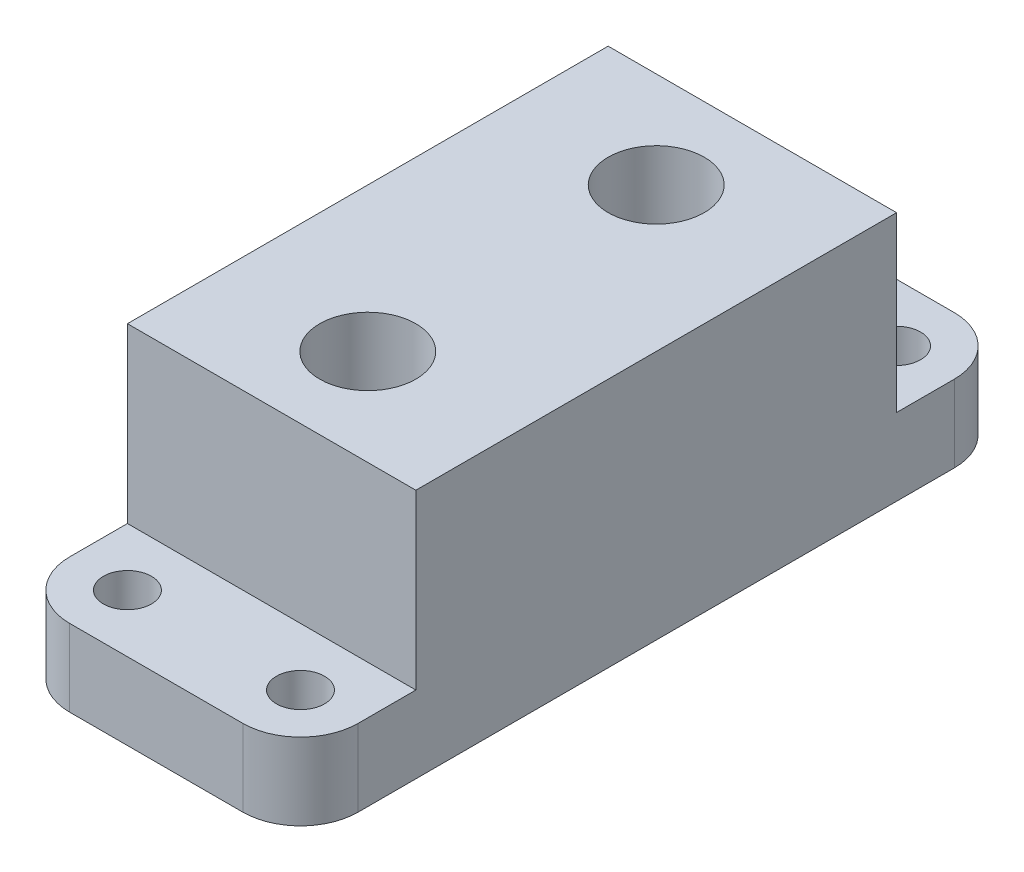
SolidWorks part; units mm, degrees
ref_plane "前视基准面" through (0, 0, 0) normal (0, 0, 1) x (1, 0, 0)
ref_plane "上视基准面" through (0, 0, 0) normal (0, 1, 0) x (1, 0, 0)
ref_plane "右视基准面" through (0, 0, 0) normal (1, 0, 0) x (0, 0, -1)
other "Configuration Table"
sketch "草图1" plane through (0, 0, 0) normal (0, 1, 0) x (1, 0, 0)
  line L1 (-32.5, 12.5) -> (32.5, 12.5)
  line L2 (-32.5, 12.5) -> (-32.5, -12.5)
  line L3 (-32.5, -12.5) -> (32.5, -12.5)
  line L4 (32.5, 12.5) -> (32.5, -12.5)
  line L5 (0, -12.5) -> (0, 12.5) construction
  line L6 (-32.5, 0) -> (32.5, 0) construction
  point P0 (0, 0)
  dimension "D1" = 25
  dimension "D2" = 65
extrude "凸台-拉伸1" add sketch "草图1" along normal blind 4
sketch "草图2" plane through (0, 4, 0) normal (0, 1, 0) x (1, 0, 0)
  line L0 (-32.5, -12.5) -> (32.5, -12.5) construction
  line L1 (-7.5, 12.5) -> (7.5, 12.5)
  line L2 (-7.5, 12.5) -> (-7.5, -12.5)
  line L3 (-7.5, -12.5) -> (7.5, -12.5)
  line L4 (7.5, 12.5) -> (7.5, -12.5)
  line L5 (0, -12.5) -> (0, 12.5) construction
  line L6 (-7.5, 0) -> (7.5, 0) construction
  point P0 (0, 0)
  dimension "D1" = 15
extrude "凸台-拉伸2" add sketch "草图2" along normal blind 13
sketch "草图3" plane through (0, 0, 0) normal (0, -1, 0) x (1, 0, 0)
  line L0 (0, 12.5) -> (0, -12.5) construction
  line L1 (-32.5, 12.5) -> (32.5, 12.5) construction
  line L2 (32.5, -12.5) -> (-32.5, -12.5) construction
  line L3 (-32.5, 0) -> (32.5, 0) construction
  line L4 (-32.5, -12.5) -> (-32.5, 12.5) construction
  line L5 (32.5, 12.5) -> (32.5, -12.5) construction
  circle A0 centre (0, -7.5) radius 2.5
  circle A1 centre (0, 7.5) radius 2.5
  circle A2 centre (-22, 0) radius 4
  circle A3 centre (22, 0) radius 4
  dimension "D1" = 5
  dimension "D3" = 8
  dimension "D2" = 5
  dimension "D4" = 22
extrude "切除-拉伸1" cut sketch "草图3" against normal through all
sketch "草图5" plane through (0, 0, 12.5) normal (0, 0, 1) x (1, 0, 0)
  line L0 (7.5, 17) -> (7.5, 4) construction
  line L1 (-7.5, 4) -> (7.5, 4)
  line L2 (-7.5, 4) -> (-7.5, 8)
  line L3 (-7.5, 8) -> (7.5, 8)
  line L4 (7.5, 4) -> (7.5, 8)
  dimension "D1" = 4
extrude "凸台-拉伸3" add sketch "草图5" along normal blind 6
sketch "草图6" plane through (0, 4, 0) normal (0, -1, 0) x (1, 0, 0)
  line L0 (0, 18.5) -> (0, 12.5) construction
  line L1 (-7.5, 18.5) -> (7.5, 18.5) construction
  line L2 (-32.5, 12.5) -> (32.5, 12.5) construction
  line L3 (-7.5, 18.5) -> (-7.5, 12.5) construction
  circle A0 centre (-4.5, 15.5) radius 1.25
  circle A1 centre (4.5, 15.5) radius 1.25
  point P11 (-7.5, 15.5)
  dimension "D1" = 2.5
  dimension "D2" = 3
extrude "切除-拉伸3" cut sketch "草图6" against normal through all
ref_plane "基准面2" through (0, 0, 0) normal (0, 0, 1) x (1, 0, 0)
mirror "镜向2" about plane through (0, 0, 0) normal (0, 0, 1) of "凸台-拉伸3", "切除-拉伸3"
fillet "圆角2" radius 3 4 edges at (-7.5, 6, -18.5) (7.5, 6, -18.5) (-7.5, 6, 18.5) (7.5, 6, 18.5)
sketch "草图7" plane through (0, 0, -12.5) normal (0, 0, -1) x (-1, 0, 0)
  line L6 (32.5, 4) -> (7.5, 4)
  line L7 (7.5, 4) -> (-7.5, 4)
  line L8 (-7.5, 4) -> (-32.5, 4)
  line L9 (-32.5, 4) -> (-32.5, 0)
  line L10 (-32.5, 0) -> (32.5, 0)
  line L11 (32.5, 0) -> (32.5, 4)
  line L12 (32.5, 4) -> (7.5, 4)
  line L13 (7.5, 4) -> (-7.5, 4)
  line L14 (-7.5, 4) -> (-32.5, 4)
  line L15 (-32.5, 4) -> (-32.5, 0)
  line L16 (-32.5, 0) -> (32.5, 0)
  line L17 (32.5, 0) -> (32.5, 4)
  dimension "D1" = 0
extrude "切除-拉伸4" cut sketch "草图7" against normal through all
